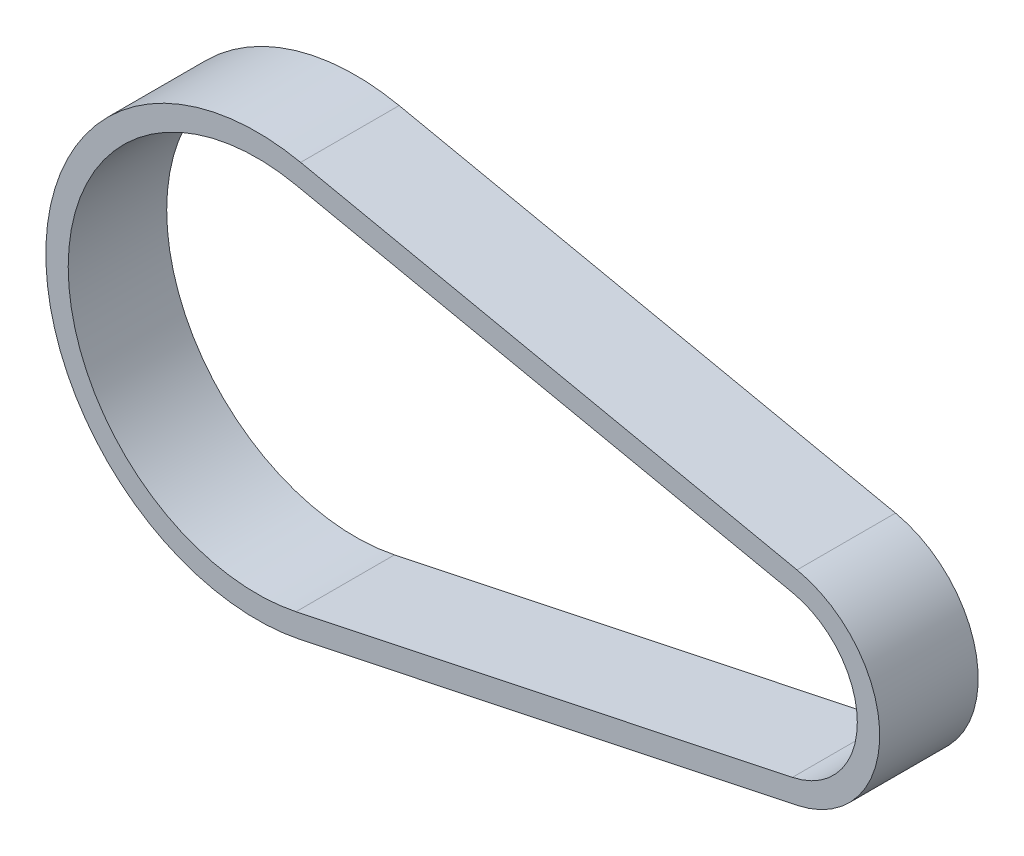
SolidWorks part; units mm, degrees
material "Natural Rubber"
ref_plane "Front" through (0, 0, 0) normal (0, 0, 1) x (1, 0, 0)
ref_plane "Top" through (0, 0, 0) normal (0, 1, 0) x (1, 0, 0)
ref_plane "Right" through (0, 0, 0) normal (1, 0, 0) x (0, 0, -1)
sketch "Sketch1" plane through (0, 0, 0) normal (0, 0, 1) x (1, 0, 0)
  line L0 (4.3543, 20.6375) -> (59.7981, 8.9394)
  line L1 (4.3543, -20.6375) -> (59.7981, -8.9394)
  line L2 (4.8704, 23.0837) -> (60.3142, 11.3855)
  line L3 (4.8704, -23.0837) -> (60.3142, -11.3855)
  line L4 (-23.5919, 0) -> (69.5482, 0) construction
  arc A0 (4.3543, 20.6375) -> (4.3543, -20.6375) centre (0, 0) ccw
  arc A1 (59.7981, -8.9394) -> (59.7981, 8.9394) centre (57.912, 0) ccw
  arc A2 (60.3142, -11.3855) -> (60.3142, 11.3855) centre (57.912, 0) ccw
  arc A3 (4.8704, 23.0837) -> (4.8704, -23.0837) centre (0, 0) ccw
  dimension "D1" = 11.6362
  dimension "D2" = 9.1362
  dimension "D3" = 23.5919
  dimension "D4" = 21.0919
  dimension "D7" = 57.912
  dimension "D5" = 2.5
  dimension "D6" = 2.5
  dimension "D8" = 93.1401
extrude "Boss-Extrude1" add sketch "Sketch1" along normal blind 11
sketch "Sketch2" plane through (0, 0, 11) normal (0, 0, 1) x (1, 0, 0)
  line L0 (69.5482, 0) -> (-23.5919, 0) construction
  arc A0 (60.3142, -11.3855) -> (60.3142, 11.3855) centre (57.912, 0) ccw construction
  arc A1 (4.8704, 23.0837) -> (4.8704, -23.0837) centre (0, 0) ccw construction
